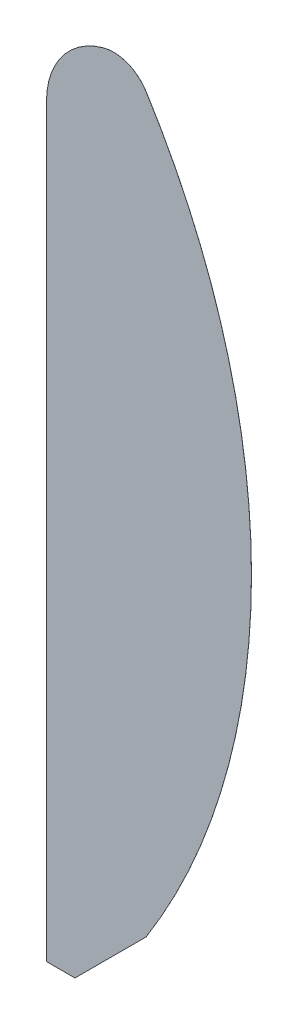
SolidWorks part; units mm, degrees
ref_plane "Front Plane" through (0, 0, 0) normal (1, 0, 0) x (0, 1, 0)
ref_plane "Top Plane" through (0, 0, 0) normal (0, 0, 1) x (0, 1, 0)
ref_plane "Right Plane" through (0, 0, 0) normal (0, 1, 0) x (-1, 0, 0)
sketch "Sketch1" plane through (0, 0, 0) normal (0, 0, 1) x (0, 1, 0)
  line L0 (0, 0) -> (0, 46433.2994) construction
  line L1 (0, 0) -> (-46433.2994, 0) construction
  line L2 (341.0561, 447.2498) -> (1519.4065, 281.6435) construction
  line L3 (0, 0) -> (130.896, 0)
  line L9 (0, 0) -> (0, -5)
  line L10 (0, -5) -> (12.5, -17.5)
  line L11 (0, 0) -> (76.7884, -36)
  arc A0 (130.896, 0) -> (144, -10) centre (130.896, -13.5857) cw
  arc A1 (144, -10) -> (141.0768, -17.5) centre (137.4886, -11.7818) cw
  arc A2 (12.5, -17.5) -> (141.0768, -17.5) centre (76.7884, 84.9526) ccw
  dimension "D1" = 130.896
  dimension "D2" = 5
  dimension "D3" = 36
  dimension "D4" = 17.5
  dimension "Span" = 144
  dimension "D6" = 12.5
  dimension "D7" = 10
extrude "Boss-Extrude1" add sketch "Sketch1" along normal blind 0.01 contours L3 A0 A1 A2 L10 L9
equation "\"D3@Sketch1\"=\"Span@Sketch1\"/4"
equation "\"D1@Sketch1\"=\"Span@Sketch1\"*0.909"
